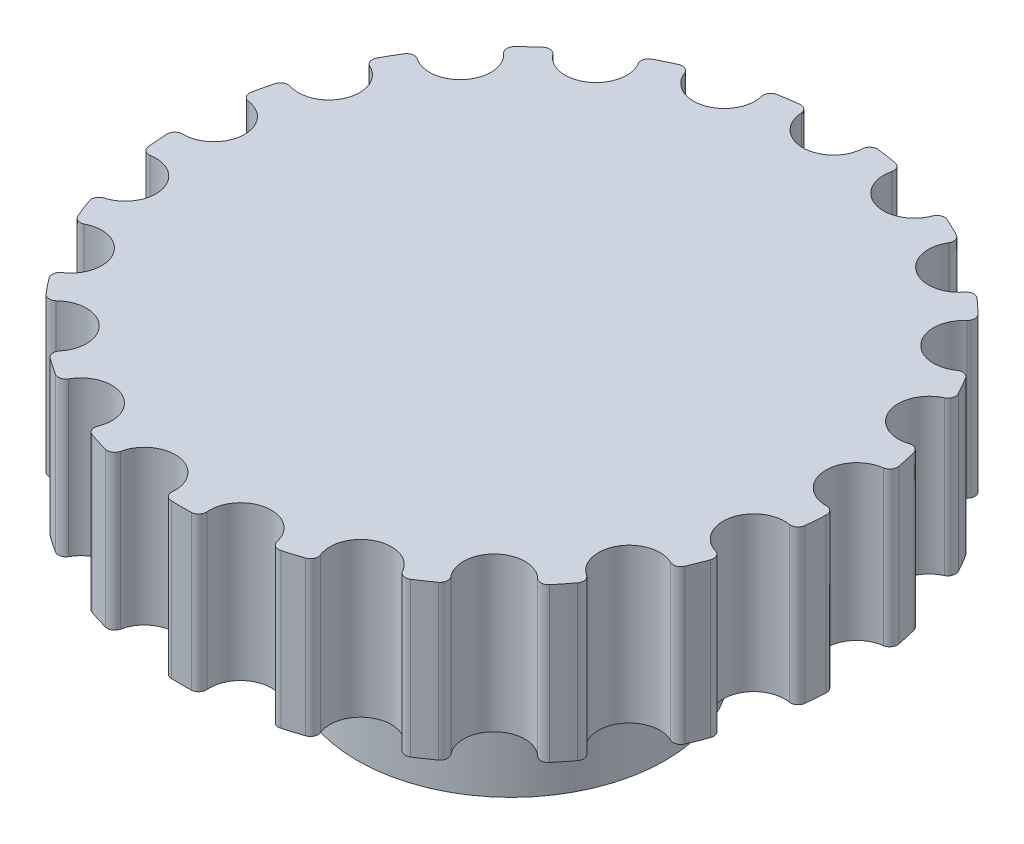
SolidWorks part; units mm, degrees
ref_plane "Front Plane" through (0, 0, 0) normal (0, 0, 1) x (1, 0, 0)
ref_plane "Top Plane" through (0, 0, 0) normal (0, 1, 0) x (1, 0, 0)
ref_plane "Right Plane" through (0, 0, 0) normal (1, 0, 0) x (0, 0, -1)
sketch "Sketch1" plane through (0, 0, 0) normal (0, 1, 0) x (1, 0, 0)
  line L0 (0, 0) -> (0, 6.6845) construction
  line L1 (0.5993, 6.2518) -> (0, 0) construction
  line L2 (1.2701, 6.1507) -> (0, 0) construction
  line L3 (0, 0) -> (-0.5993, 6.2518) construction
  circle A0 centre (0, 0) radius 6.6845 construction
  circle A2 centre (0, 0) radius 6.4305 construction
  circle A3 centre (0, 0) radius 5.6805 construction
  circle A4 centre (0, 0) radius 6.2805 construction
  arc A5 (0.5993, 6.2518) -> (0.7663, 6.3847) centre (0.7484, 6.2358) cw
  arc A6 (0.7663, 6.3847) -> (1.1496, 6.3269) centre (0, 0) cw
  arc A7 (1.1496, 6.3269) -> (1.2701, 6.1507) centre (1.1228, 6.1793) cw
  arc A8 (0.5993, 6.2518) -> (-0.5993, 6.2518) centre (0, 6.2805) cw
  arc A9 (2.4155, 5.7974) -> (1.2701, 6.1507) centre (1.8512, 6.0015) cw
  arc A10 (2.4155, 5.7974) -> (2.6142, 5.8752) centre (2.5532, 5.7381) cw
  arc A11 (2.6142, 5.8752) -> (2.9635, 5.707) centre (0, 0) cw
  arc A12 (2.9635, 5.707) -> (3.0266, 5.5031) centre (2.8943, 5.5738) cw
  arc A13 (4.017, 4.8279) -> (3.0266, 5.5031) centre (3.5379, 5.1892) cw
  arc A14 (4.017, 4.8279) -> (4.2298, 4.8436) centre (4.1311, 4.7306) cw
  arc A15 (4.2298, 4.8436) -> (4.514, 4.5799) centre (0, 0) cw
  arc A16 (4.514, 4.5799) -> (4.5142, 4.3665) centre (4.4087, 4.4731) cw
  arc A17 (5.2616, 3.4294) -> (4.5142, 4.3665) centre (4.9103, 3.9158) cw
  arc A18 (5.2616, 3.4294) -> (5.4695, 3.3816) centre (5.342, 3.3028) cw
  arc A19 (5.4695, 3.3816) -> (5.6634, 3.0459) centre (0, 0) cw
  arc A20 (5.6634, 3.0459) -> (5.6007, 2.8419) centre (5.5313, 2.9749) cw
  arc A21 (6.0386, 1.7262) -> (5.6007, 2.8419) centre (5.8464, 2.2945) cw
  arc A22 (6.0386, 1.7262) -> (6.2233, 1.6192) centre (6.0781, 1.5815) cw
  arc A23 (6.2233, 1.6192) -> (6.3096, 1.2413) centre (0, 0) cw
  arc A24 (6.3096, 1.2413) -> (6.1896, 1.0648) centre (6.1624, 1.2124) cw
  arc A25 (6.2792, -0.1304) -> (6.1896, 1.0648) centre (6.2629, 0.4693) cw
  arc A26 (6.2792, -0.1304) -> (6.4241, -0.2871) centre (6.2742, -0.2804) cw
  arc A27 (6.4241, -0.2871) -> (6.3951, -0.6736) centre (0, 0) cw
  arc A28 (6.3951, -0.6736) -> (6.2285, -0.8069) centre (6.246, -0.6579) cw
  arc A29 (5.9617, -1.9755) -> (6.2285, -0.8069) centre (6.123, -1.3975) cw
  arc A30 (5.9617, -1.9755) -> (6.0541, -2.1678) centre (5.9129, -2.1173) cw
  arc A31 (6.0541, -2.1678) -> (5.9125, -2.5287) centre (0, 0) cw
  arc A32 (5.9125, -2.5287) -> (5.7139, -2.6069) centre (5.7745, -2.4697) cw
  arc A33 (5.1146, -3.6449) -> (5.7139, -2.6069) centre (5.4391, -3.1403) cw
  arc A34 (5.1146, -3.6449) -> (5.1461, -3.856) centre (5.0261, -3.7661) cw
  arc A35 (5.1461, -3.856) -> (4.9044, -4.1591) centre (0, 0) cw
  arc A36 (4.9044, -4.1591) -> (4.6917, -4.1753) centre (4.79, -4.0621) cw
  arc A37 (3.813, -4.9906) -> (4.6917, -4.1753) centre (4.2718, -4.6039) cw
  arc A38 (3.813, -4.9906) -> (3.7809, -5.2015) centre (3.6927, -5.0802) cw
  arc A39 (3.7809, -5.2015) -> (3.4606, -5.4199) centre (0, 0) cw
  arc A40 (3.4606, -5.4199) -> (3.2525, -5.3727) centre (3.3799, -5.2935) cw
  arc A41 (2.1726, -5.8928) -> (3.2525, -5.3727) centre (2.725, -5.6585) cw
  arc A42 (2.1726, -5.8928) -> (2.0798, -6.0849) centre (2.0313, -5.943) cw
  arc A43 (2.0798, -6.0849) -> (1.7094, -6.1992) centre (0, 0) cw
  arc A44 (1.7094, -6.1992) -> (1.5244, -6.0927) centre (1.6695, -6.0546) cw
  arc A45 (0.3392, -6.2713) -> (1.5244, -6.0927) centre (0.9361, -6.2104) cw
  arc A46 (0.3392, -6.2713) -> (0.1938, -6.4276) centre (0.1893, -6.2777) cw
  arc A47 (0.1938, -6.4276) -> (-0.1938, -6.4276) centre (0, 0) cw
  arc A48 (-0.1938, -6.4276) -> (-0.3392, -6.2713) centre (-0.1893, -6.2777) cw
  arc A49 (-1.5244, -6.0927) -> (-0.3392, -6.2713) centre (-0.9361, -6.2104) cw
  arc A50 (-1.5244, -6.0927) -> (-1.7094, -6.1992) centre (-1.6695, -6.0546) cw
  arc A51 (-1.7094, -6.1992) -> (-2.0798, -6.0849) centre (0, 0) cw
  arc A52 (-2.0798, -6.0849) -> (-2.1726, -5.8928) centre (-2.0313, -5.943) cw
  arc A53 (-3.2525, -5.3727) -> (-2.1726, -5.8928) centre (-2.725, -5.6585) cw
  arc A54 (-3.2525, -5.3727) -> (-3.4606, -5.4199) centre (-3.3799, -5.2935) cw
  arc A55 (-3.4606, -5.4199) -> (-3.7809, -5.2015) centre (0, 0) cw
  arc A56 (-3.7809, -5.2015) -> (-3.813, -4.9906) centre (-3.6927, -5.0802) cw
  arc A57 (-4.6917, -4.1753) -> (-3.813, -4.9906) centre (-4.2718, -4.6039) cw
  arc A58 (-4.6917, -4.1753) -> (-4.9044, -4.1591) centre (-4.79, -4.0621) cw
  arc A59 (-4.9044, -4.1591) -> (-5.1461, -3.856) centre (0, 0) cw
  arc A60 (-5.1461, -3.856) -> (-5.1146, -3.6449) centre (-5.0261, -3.7661) cw
  arc A61 (-5.7139, -2.6069) -> (-5.1146, -3.6449) centre (-5.4391, -3.1403) cw
  arc A62 (-5.7139, -2.6069) -> (-5.9125, -2.5287) centre (-5.7745, -2.4697) cw
  arc A63 (-5.9125, -2.5287) -> (-6.0541, -2.1678) centre (0, 0) cw
  arc A64 (-6.0541, -2.1678) -> (-5.9617, -1.9755) centre (-5.9129, -2.1173) cw
  arc A65 (-6.2285, -0.8069) -> (-5.9617, -1.9755) centre (-6.123, -1.3975) cw
  arc A66 (-6.2285, -0.8069) -> (-6.3951, -0.6736) centre (-6.246, -0.6579) cw
  arc A67 (-6.3951, -0.6736) -> (-6.4241, -0.2871) centre (0, 0) cw
  arc A68 (-6.4241, -0.2871) -> (-6.2792, -0.1304) centre (-6.2742, -0.2804) cw
  arc A69 (-6.1896, 1.0648) -> (-6.2792, -0.1304) centre (-6.2629, 0.4693) cw
  arc A70 (-6.1896, 1.0648) -> (-6.3096, 1.2413) centre (-6.1624, 1.2124) cw
  arc A71 (-6.3096, 1.2413) -> (-6.2233, 1.6192) centre (0, 0) cw
  arc A72 (-6.2233, 1.6192) -> (-6.0386, 1.7262) centre (-6.0781, 1.5815) cw
  arc A73 (-5.6007, 2.8419) -> (-6.0386, 1.7262) centre (-5.8464, 2.2945) cw
  arc A74 (-5.6007, 2.8419) -> (-5.6634, 3.0459) centre (-5.5313, 2.9749) cw
  arc A75 (-5.6634, 3.0459) -> (-5.4695, 3.3816) centre (0, 0) cw
  arc A76 (-5.4695, 3.3816) -> (-5.2616, 3.4294) centre (-5.342, 3.3028) cw
  arc A77 (-4.5142, 4.3665) -> (-5.2616, 3.4294) centre (-4.9103, 3.9158) cw
  arc A78 (-4.5142, 4.3665) -> (-4.514, 4.5799) centre (-4.4087, 4.4731) cw
  arc A79 (-4.514, 4.5799) -> (-4.2298, 4.8436) centre (0, 0) cw
  arc A80 (-4.2298, 4.8436) -> (-4.017, 4.8279) centre (-4.1311, 4.7306) cw
  arc A81 (-3.0266, 5.5031) -> (-4.017, 4.8279) centre (-3.5379, 5.1892) cw
  arc A82 (-3.0266, 5.5031) -> (-2.9635, 5.707) centre (-2.8943, 5.5738) cw
  arc A83 (-2.9635, 5.707) -> (-2.6142, 5.8752) centre (0, 0) cw
  arc A84 (-2.6142, 5.8752) -> (-2.4155, 5.7974) centre (-2.5532, 5.7381) cw
  arc A85 (-1.2701, 6.1507) -> (-2.4155, 5.7974) centre (-1.8512, 6.0015) cw
  arc A86 (-1.2701, 6.1507) -> (-1.1496, 6.3269) centre (-1.1228, 6.1793) cw
  arc A87 (-1.1496, 6.3269) -> (-0.7663, 6.3847) centre (0, 0) cw
  arc A88 (-0.7663, 6.3847) -> (-0.5993, 6.2518) centre (-0.7484, 6.2358) cw
  point P178 (0, 0)
  dimension "D1" = 0.75
  dimension "D2" = 0.254
  dimension "D3" = 17.143
  dimension "D4" = 0.6
  dimension "D6" = 13.369
  dimension "D5" = 21
extrude "Boss-Extrude1" add sketch "Sketch1" along normal blind 3
sketch "Sketch2" plane through (0, 0, 0) normal (0, -1, 0) x (-1, 0, 0)
  circle A0 centre (0, 0) radius 3
  dimension "D1" = 6
extrude "Boss-Extrude2" add sketch "Sketch2" along normal blind 3
